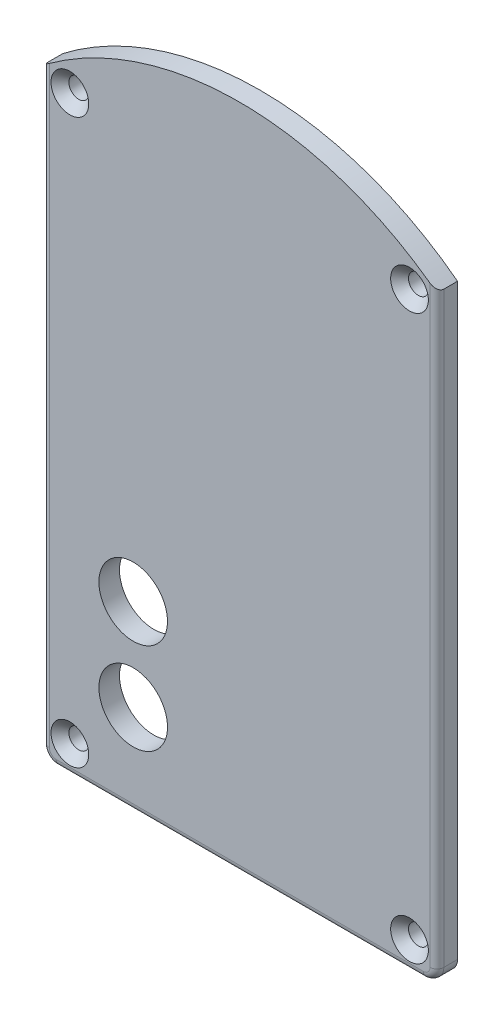
SolidWorks part; units mm, degrees
ref_plane "Piano frontale" through (0, 0, 0) normal (0, 0, 1) x (1, 0, 0)
ref_plane "Piano superiore" through (0, 0, 0) normal (0, 1, 0) x (1, 0, 0)
ref_plane "Piano destro" through (0, 0, 0) normal (1, 0, 0) x (0, 0, -1)
sketch "Schizzo4" plane through (0, 0, 0) normal (0, 0, 1) x (1, 0, 0)
  line L7 (-28.75, 50) -> (28.75, 50)
  line L8 (-28.75, 50) -> (-28.75, -50)
  line L13 (-28.75, -50) -> (28.75, -50)
  line L14 (28.75, 50) -> (28.75, -50)
  line L15 (-28.75, 50) -> (28.75, -50) construction
  line L16 (-28.75, -50) -> (28.75, 50) construction
  point P0 (0, 0)
  dimension "D1" = 57.5
  dimension "D2" = 100
extrude "Estrusione-Estrusione2" add sketch "Schizzo4" along normal blind 3 separate body
sketch "Schizzo7" plane through (0, 0, 0) normal (0, 0, 1) x (1, 0, 0)
  line L2 (-28.75, 50) -> (-28.75, -50) construction
  line L7 (28.75, -50) -> (28.75, 50) construction
  line L8 (-28.75, -50) -> (28.75, -50) construction
  line L16 (-28.75, 37.61) -> (-28.75, 50)
  line L17 (-28.75, 50) -> (28.75, 50)
  line L18 (28.75, 50) -> (28.75, 37.61)
  circle A4 centre (-15.52, -36.81) radius 5
  circle A5 centre (-15.52, -23.47) radius 5
  arc A112 (-28.75, 37.61) -> (28.75, 37.61) centre (0, 0) cw
  point P5 (-28.75, 37.3831)
  point P6 (0, 0)
  point P12 (0, 0)
  point P15 (0, 0)
  dimension "D1" = 13.23
  dimension "D2" = 13.34
  dimension "D4" = 10
  dimension "D5" = 47.34
  dimension "D3" = 13.19
extrude "Taglio-Estrusione2" cut sketch "Schizzo7" along normal up to next
fillet "Raccordo1" radius 2 1 edges at (-28.75, -50, 1.5)
fillet "Raccordo3" radius 2 1 edges at (28.75, -50, 1.5)
fillet "Raccordo4" radius 1 5 edges at (-28.75, -5.195, 3) (0, -50, 3) (-28.1642, -49.4142, 3) (28.75, -5.195, 3) (28.1642, -49.4142, 3)
hole_wizard "Foro svasato per Vite M2.5-1" positions "Schizzo9" profile "Schizzo10" countersink size "M2.5" standard "Ansi Metric" end condition up to next
sketch "Schizzo9" plane through (0, 0, 3) normal (0, 0, 1) x (1, 0, 0)
  line L0 (28.75, 37.61) -> (28.75, -48) construction
  line L1 (26.75, -50) -> (-26.75, -50) construction
  point P0 (-24.75, 36.11)
  point P2 (24.75, -46)
  point P4 (-24.75, -46)
  point P10 (24.75, 36.11)
  dimension "D1" = 1.5
  dimension "D2" = 4
  dimension "D3" = 4
  dimension "D4" = 4
sketch "Schizzo10" plane through (-24.75, 36.11, 3) normal (1, 0, 0) x (0, -1, 0)
  line L0 (0, 0) -> (0, 3)
  line L1 (0, 3) -> (1.45, 3)
  line L2 (1.45, 3) -> (1.45, 1.3)
  line L3 (1.45, 1.3) -> (2.75, 0)
  line L5 (2.75, 0) -> (0, 0)
  line L6 (-1.45, 1.3) -> (-2.75, 0) construction
  line L11 (0, -6.35) -> (0, 107.95) construction
  dimension "Thru Hole Dia." = 2.9
  dimension "Thru Hole Depth" = 3
  dimension "Near C'Sink Dia." = 5.5
  dimension "Near C'Sink Angle" = 90
